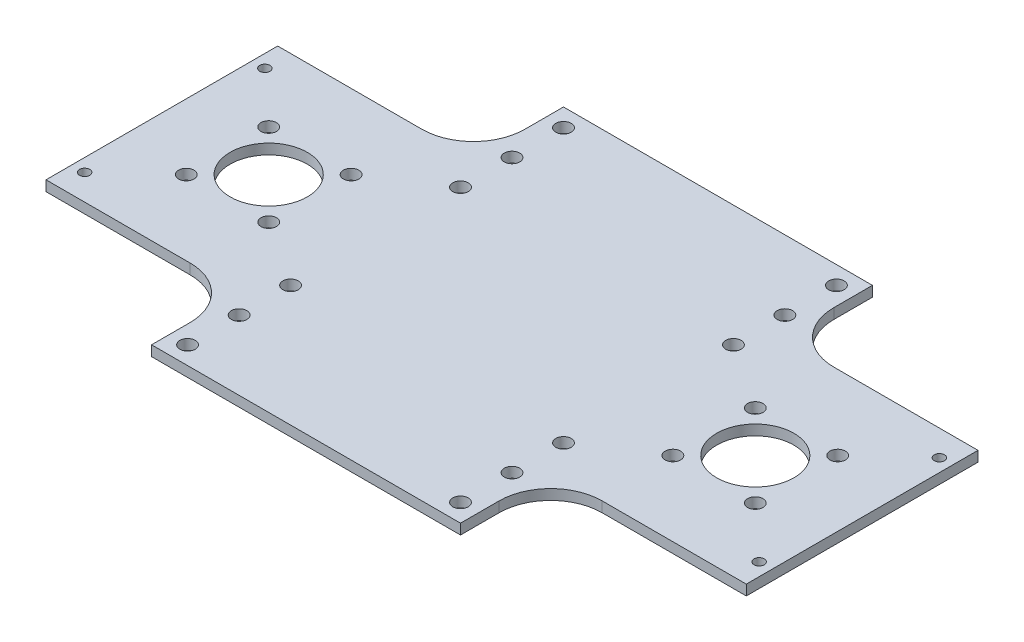
SolidWorks part; units mm, degrees
ref_plane "Front Plane" through (0, 0, 0) normal (0, 0, 1) x (1, 0, 0)
ref_plane "Top Plane" through (0, 0, 0) normal (0, 1, 0) x (1, 0, 0)
ref_plane "Right Plane" through (0, 0, 0) normal (1, 0, 0) x (0, 0, -1)
sketch "Sketch1" plane through (0, 0, 0) normal (0, 1, 0) x (1, 0, 0)
  line L0 (98, 45) -> (136, 45)
  line L1 (0, 0) -> (38, 0)
  line L2 (0, 0) -> (0, 45)
  line L3 (0, 45) -> (38, 45)
  line L4 (136, 0) -> (136, 45)
  line L5 (98, 0) -> (136, 0)
  line L6 (38, 45) -> (38, 62.5)
  line L7 (38, 62.5) -> (98, 62.5)
  line L8 (98, 45) -> (98, 62.5)
  line L10 (38, 0) -> (38, -17.5)
  line L11 (38, -17.5) -> (98, -17.5)
  line L12 (98, 0) -> (98, -17.5)
  dimension "D1" = 136
  dimension "D2" = 45
  dimension "D3" = 17.5
  dimension "D4" = 60
  dimension "D5" = 38
  dimension "D6" = 38
  dimension "D7" = 60
  dimension "D8" = 38
  dimension "D9" = 17.5
  dimension "D10" = 80
  dimension "D11" = 38
  dimension "D12" = 80
extrude "Boss-Extrude1" add sketch "Sketch1" along normal blind 2
hole_wizard "M2 Clearance Hole1" positions "Sketch3" profile "Sketch2" hole size "M2" standard "ANSI Metric"
sketch "Sketch3" plane through (0, 2, 0) normal (0, 1, 0) x (1, 0, 0)
  line L0 (38, 45) -> (0, 45) construction
  line L1 (0, 0) -> (38, 0) construction
  line L2 (0, 45) -> (0, 0) construction
  line L3 (136, 0) -> (136, 45) construction
  line L4 (136, 45) -> (98, 45) construction
  line L5 (98, 0) -> (136, 0) construction
  point P0 (2.5, 5)
  point P2 (2.5, 40)
  point P4 (133.5, 40)
  point P6 (133.5, 5)
  dimension "D1" = 35
  dimension "D2" = 5
  dimension "D3" = 5
  dimension "D4" = 2.5
  dimension "D5" = 2.5
  dimension "D6" = 2.5
  dimension "D7" = 2.5
  dimension "D8" = 35
  dimension "D9" = 5
  dimension "D10" = 5
sketch "Sketch2" plane through (2.5, 2, -5) normal (1, 0, 0) x (0, 0, 1)
  line L0 (0, 0) -> (0, 2.6009)
  line L1 (0, 2.6009) -> (1, 2)
  line L2 (1, 2) -> (1, 0)
  line L5 (1, 0) -> (0, 0)
  line L10 (0, 2.6009) -> (-1, 2) construction
  line L11 (0, -6.35) -> (0, 107.95) construction
  dimension "Hole Dia." = 2
  dimension "Hole Depth" = 2
  dimension "Drill Angle" = 118
hole_wizard "M3 Clearance Hole1" positions "Sketch5" profile "Sketch4" hole size "M3" standard "ANSI Metric" end condition through all
sketch "Sketch5" plane through (0, 2, 0) normal (0, 1, 0) x (1, 0, 0)
  line L0 (38, 62.5) -> (38, 45) construction
  line L1 (98, 45) -> (98, 62.5) construction
  line L2 (0, 0) -> (38, 0) construction
  line L3 (38, -17.5) -> (98, -17.5) construction
  point P0 (41.5, 39)
  point P2 (94.5, 39)
  point P4 (94.5, -14)
  point P6 (41.5, -14)
  dimension "D1" = 53
  dimension "D2" = 53
  dimension "D3" = 53
  dimension "D4" = 53
  dimension "D5" = 3.5
  dimension "D6" = 3.5
  dimension "D7" = 3.5
  dimension "D8" = 14
sketch "Sketch4" plane through (41.5, 2, -39) normal (1, 0, 0) x (0, 0, 1)
  line L0 (0, 0) -> (0, 2)
  line L1 (0, 2) -> (1.5, 2)
  line L2 (1.5, 2) -> (1.5, 0)
  line L5 (1.5, 0) -> (0, 0)
  line L11 (0, -6.35) -> (0, 107.95) construction
  dimension "Thru Hole Dia." = 3
  dimension "Thru Hole Depth" = 2
hole_wizard "M3 Clearance Hole2" positions "Sketch7" profile "Sketch6" hole size "M3" standard "ANSI Metric"
sketch "Sketch7" plane through (0, 2, 0) normal (0, 1, 0) x (1, 0, 0)
  line L0 (38, 0) -> (38, -17.5) construction
  line L1 (98, -17.5) -> (98, 0) construction
  line L2 (98, 45) -> (98, 62.5) construction
  line L3 (38, 62.5) -> (38, 45) construction
  line L4 (98, 62.5) -> (38, 62.5) construction
  line L5 (38, -17.5) -> (98, -17.5) construction
  point P0 (41.5, -4)
  point P2 (94.5, -4)
  point P4 (94.5, 49)
  point P6 (41.5, 49)
  dimension "D5" = 3.5
  dimension "D1" = 53
  dimension "D2" = 53
  dimension "D3" = 53
  dimension "D4" = 53
  dimension "D6" = 3.5
  dimension "D7" = 3.5
  dimension "D8" = 3.5
  dimension "D9" = 13.5
  dimension "D10" = 13.5
sketch "Sketch6" plane through (41.5, 2, 4) normal (1, 0, 0) x (0, 0, 1)
  line L0 (0, 0) -> (0, 2.9013)
  line L1 (0, 2.9013) -> (1.5, 2)
  line L2 (1.5, 2) -> (1.5, 0)
  line L5 (1.5, 0) -> (0, 0)
  line L10 (0, 2.9013) -> (-1.5, 2) construction
  line L11 (0, -6.35) -> (0, 107.95) construction
  dimension "Hole Dia." = 3
  dimension "Hole Depth" = 2
  dimension "Drill Angle" = 118
hole_wizard "M3 Clearance Hole3" positions "Sketch9" profile "Sketch8" hole size "M3" standard "ANSI Metric"
sketch "Sketch9" plane through (0, 2, 0) normal (0, 1, 0) x (1, 0, 0)
  line L0 (98, 62.5) -> (38, 62.5) construction
  line L1 (98, 45) -> (98, 62.5) construction
  point P0 (41.5, 59)
  point P2 (94.5, 59)
  point P4 (94.5, 6)
  point P6 (41.5, 6)
  dimension "D1" = 53
  dimension "D2" = 53
  dimension "D3" = 53
  dimension "D4" = 53
  dimension "D5" = 3.5
  dimension "D6" = 3.5
sketch "Sketch8" plane through (41.5, 2, -59) normal (1, 0, 0) x (0, 0, 1)
  line L0 (0, 0) -> (0, 2.9013)
  line L1 (0, 2.9013) -> (1.5, 2)
  line L2 (1.5, 2) -> (1.5, 0)
  line L5 (1.5, 0) -> (0, 0)
  line L10 (0, 2.9013) -> (-1.5, 2) construction
  line L11 (0, -6.35) -> (0, 107.95) construction
  dimension "Hole Dia." = 3
  dimension "Hole Depth" = 2
  dimension "Drill Angle" = 118
fillet "Fillet1" radius 10 1 edges at (98, 1, 0)
fillet "Fillet2" radius 10 1 edges at (98, 1, -45)
fillet "Fillet3" radius 10 1 edges at (38, 1, 0)
fillet "Fillet4" radius 10 1 edges at (38, 1, -45)
hole_wizard "M14 Clearance Hole1" positions "Sketch12" profile "Sketch13" hole size "M14" standard "ANSI Metric" end condition through all
sketch "Sketch12" plane through (0, 2, 0) normal (0, 1, 0) x (1, 0, 0)
  line L2 (108, 0) -> (136, 0) construction
  line L3 (136, 45) -> (108, 45) construction
  line L4 (0, 0) -> (28, 0) construction
  line L5 (28, 45) -> (0, 45) construction
  line L7 (0, 45) -> (0, 0) construction
  line L8 (136, 0) -> (136, 45) construction
  line L9 (41.5, 49) -> (41.5, 6) construction
  point P0 (115.25, 22.5)
  point P2 (20.75, 22.5)
  dimension "D1" = 22.5
  dimension "D2" = 22.5
  dimension "D3" = 22.5
  dimension "D4" = 22.5
  dimension "D5" = 20.75
  dimension "D6" = 20.75
  dimension "D7" = 94.5
  dimension "D8" = 20.75
sketch "Sketch13" plane through (115.25, 2, -22.5) normal (1, 0, 0) x (0, 0, 1)
  line L0 (0, 0) -> (0, 2)
  line L1 (0, 2) -> (7.5, 2)
  line L2 (7.5, 2) -> (7.5, 0)
  line L5 (7.5, 0) -> (0, 0)
  line L11 (0, -6.35) -> (0, 107.95) construction
  dimension "Thru Hole Dia." = 15
  dimension "Thru Hole Depth" = 2
hole_wizard "M3 Clearance Hole4" positions "Sketch15" profile "Sketch14" hole size "M3" standard "ANSI Metric"
sketch "Sketch15" plane through (0, 2, 0) normal (0, 1, 0) x (1, 0, 0)
  circle A1 centre (115.25, 22.5) radius 7.5 construction
  point P0 (107.25, 30.5)
  point P2 (123.25, 30.5)
  point P4 (123.25, 14.5)
  point P6 (107.25, 14.5)
  dimension "D6" = 8
  dimension "D8" = 8
  dimension "D1" = 8
  dimension "D2" = 8
  dimension "D3" = 8
  dimension "D4" = 8
  dimension "D5" = 8
  dimension "D7" = 8
sketch "Sketch14" plane through (107.25, 2, -30.5) normal (1, 0, 0) x (0, 0, 1)
  line L0 (0, 0) -> (0, 2.9013)
  line L1 (0, 2.9013) -> (1.5, 2)
  line L2 (1.5, 2) -> (1.5, 0)
  line L5 (1.5, 0) -> (0, 0)
  line L10 (0, 2.9013) -> (-1.5, 2) construction
  line L11 (0, -6.35) -> (0, 107.95) construction
  dimension "Hole Dia." = 3
  dimension "Hole Depth" = 2
  dimension "Drill Angle" = 118
pattern_linear "LPattern1" count 2 spacing 94.5 along (-1, 0, 0) of "M3 Clearance Hole4"
